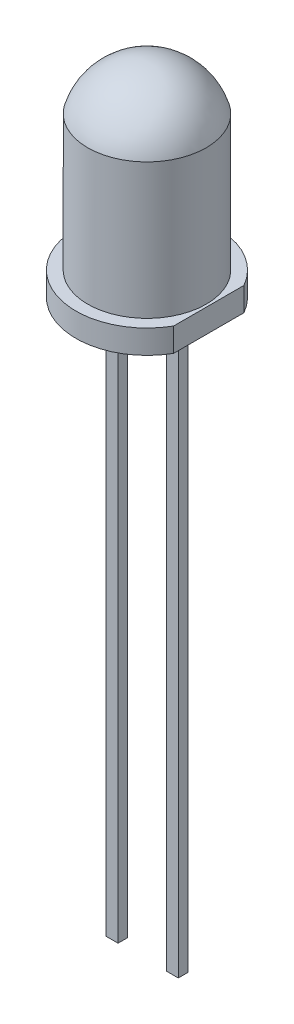
SolidWorks part; units mm, degrees
ref_plane "Alzado" through (0, 0, 0) normal (0, 0, 1) x (1, 0, 0)
ref_plane "Planta" through (0, 0, 0) normal (0, 1, 0) x (1, 0, 0)
ref_plane "Vista lateral" through (0, 0, 0) normal (1, 0, 0) x (0, 0, -1)
sketch "Croquis1" plane through (0, 0, 0) normal (0, 0, 1) x (1, 0, 0)
  line L0 (0, 0) -> (2.5, 0)
  line L1 (2.5, 0) -> (2.5, 5.7141)
  line L3 (0, 7.6) -> (0, 0)
  arc A0 (0, 7.6) -> (2.5, 5.7141) centre (0, 5) cw
revolve "Revolución1" add sketch "Croquis1" angle 360 about L3
sketch "Croquis2" plane through (0, 0, 0) normal (0, -1, 0) x (1, 0, 0)
  line L0 (2.6075, 1.4835) -> (2.6075, -1.4835)
  arc A0 (2.6075, 1.4835) -> (2.6075, -1.4835) centre (0, 0) ccw
extrude "Saliente-Extruir2" add sketch "Croquis2" along normal blind 1
sketch "Croquis3" plane through (0, -1, 0) normal (0, -1, 0) x (1, 0, 0)
  line L0 (-1.27, 0.2) -> (-1.27, 1.0164) construction
  line L1 (0, -0.8742) -> (0, 1.5651) construction
  line L2 (1.52, 0.2) -> (1.02, 0.2)
  line L3 (1.52, 0.2) -> (1.52, -0.2)
  line L4 (1.52, -0.2) -> (1.02, -0.2)
  line L5 (1.02, 0.2) -> (1.02, -0.2)
  line L6 (1.52, 0.2) -> (1.02, -0.2) construction
  line L7 (1.52, -0.2) -> (1.02, 0.2) construction
  line L8 (-1.52, -0.2) -> (-1.02, -0.2)
  line L9 (-1.52, 0.2) -> (-1.52, -0.2)
  line L10 (-1.52, 0.2) -> (-1.02, 0.2)
  line L11 (-1.02, 0.2) -> (-1.02, -0.2)
  line L12 (1.27, 0.2) -> (1.27, 1.0164) construction
  line L13 (1.27, 1.0164) -> (-1.27, 1.0164) construction
  point P14 (0, 0)
  dimension "D1" = 2.54
  dimension "D2" = 0.5
  dimension "D3" = 0.4
extrude "Saliente-Extruir3" add sketch "Croquis3" along normal blind 24
